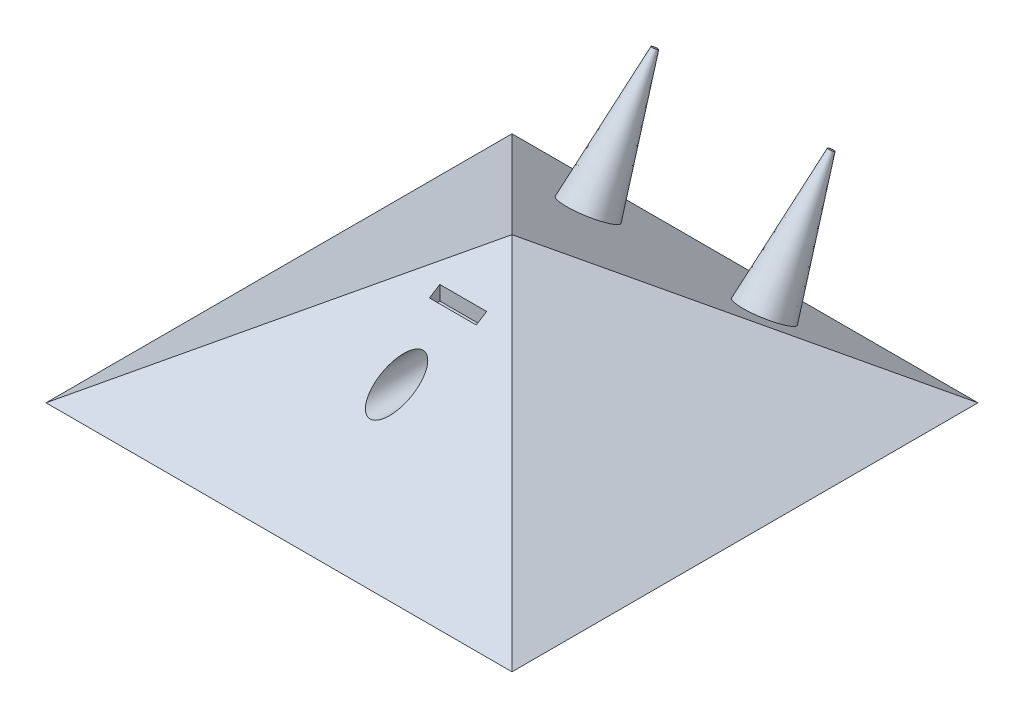
SolidWorks part; units mm, degrees
ref_plane "Plan de face" through (0, 0, 0) normal (0, 0, 1) x (1, 0, 0)
ref_plane "Plan de dessus" through (0, 0, 0) normal (0, 1, 0) x (1, 0, 0)
ref_plane "Plan de droite" through (0, 0, 0) normal (1, 0, 0) x (0, 0, -1)
sketch "Esquisse1" plane through (0, 0, 0) normal (0, 1, 0) x (1, 0, 0)
  line L1 (-23.495, -23.495) -> (23.495, -23.495)
  line L2 (-23.495, -23.495) -> (-23.495, 23.495)
  line L3 (-23.495, 23.495) -> (23.495, 23.495)
  line L4 (23.495, -23.495) -> (23.495, 23.495)
  line L5 (-23.495, -23.495) -> (23.495, 23.495) construction
  line L6 (-23.495, 23.495) -> (23.495, -23.495) construction
  point P0 (0, 0)
  dimension "D1" = 46.99
  dimension "D2" = 46.99
extrude "Boss.-Extru.1" add sketch "Esquisse1" along normal blind 14.8158 draft 58
ref_plane "Plan1" through (0, 0, 26.67) normal (0, 0, 1) x (1, 0, 0)
sketch "Esquisse4" plane through (0, 0, 26.67) normal (0, 0, 1) x (1, 0, 0)
  line L0 (-23.495, 0) -> (0, 0)
  line L1 (0, 0) -> (0, 7.4079)
  circle A0 centre (0, 7.4079) radius 1.6669
  dimension "D1" = 3.3337
sketch "Esquisse5" plane through (0, 10.5586, -6.5977) normal (0, 0.848, -0.5299) x (1, 0, 0)
  line L0 (9.4326, 11.1176) -> (-8.3474, 11.1176) construction
  circle A0 centre (9.4326, 11.1176) radius 2.54
  circle A1 centre (-8.3474, 11.1176) radius 2.54
extrude "Boss.-Extru.2" add sketch "Esquisse5" along normal blind 12.7 draft 10
ref_plane "Plan2" through (0, 15.24, 0) normal (0, 1, 0) x (1, 0, 0)
extrude "Enlèv. mat.-Extru.2" cut sketch "Esquisse4" against normal blind 20.32
sketch "Esquisse7" plane through (0, 15.24, 0) normal (0, 1, 0) x (1, 0, 0)
  line L1 (-2.3601, -4.9145) -> (2.3601, -4.9145)
  line L2 (-2.3601, -4.9145) -> (-2.3601, -5.9635)
  line L3 (-2.3601, -5.9635) -> (2.3601, -5.9635)
  line L4 (2.3601, -4.9145) -> (2.3601, -5.9635)
  line L5 (-2.3601, -4.9145) -> (2.3601, -5.9635) construction
  line L6 (-2.3601, -5.9635) -> (2.3601, -4.9145) construction
  point P0 (0, -5.439)
extrude "Enlèv. mat.-Extru.7" cut sketch "Esquisse7" against normal blind 5.08
